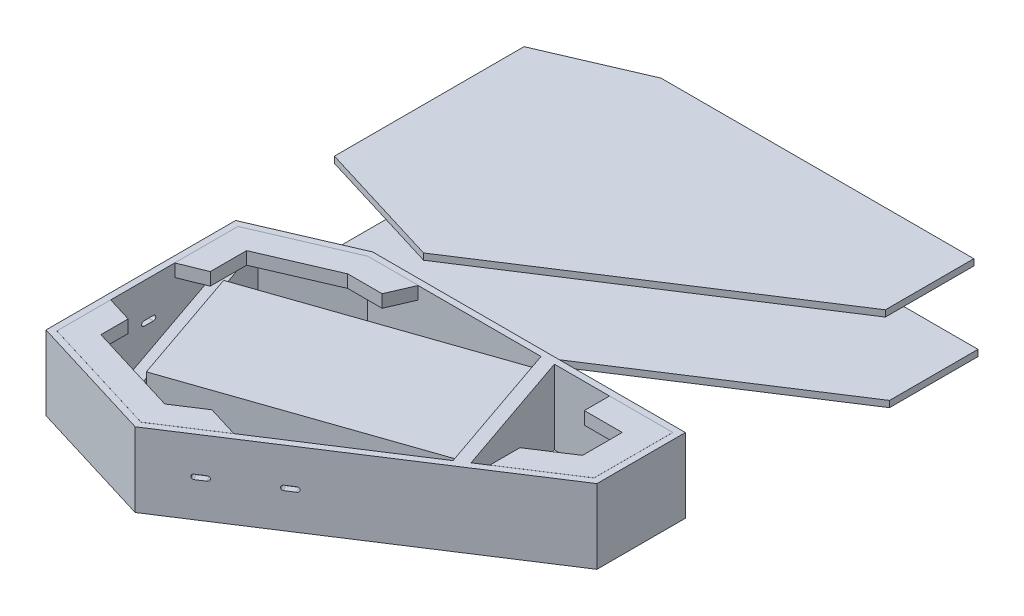
SolidWorks part; units mm, degrees
ref_plane "Front Plane" through (0, 0, 0) normal (0, 0, 1) x (1, 0, 0)
ref_plane "Top Plane" through (0, 0, 0) normal (0, 1, 0) x (1, 0, 0)
ref_plane "Right Plane" through (0, 0, 0) normal (1, 0, 0) x (0, 0, -1)
sketch "Sketch1" plane through (0, 0, 0) normal (0, 1, 0) x (1, 0, 0)
  line L0 (89.8686, 45.6481) -> (404.1936, 45.6481)
  line L1 (404.1936, 45.6481) -> (404.1936, -43.2519)
  line L2 (404.1936, -43.2519) -> (122.6914, -225.8144)
  line L3 (122.6914, -225.8144) -> (-6.35, -186.3625)
  line L4 (-6.35, -186.3625) -> (-6.35, 4.1778)
  line L5 (-6.35, 4.1778) -> (89.8686, 45.6481)
  line L6 (0, 0) -> (91.1788, 39.2981)
  line L7 (91.1788, 39.2981) -> (397.8436, 39.2981)
  line L8 (397.8436, 39.2981) -> (397.8436, -39.8016)
  line L9 (397.8436, -39.8016) -> (121.7185, -218.8769)
  line L10 (121.7185, -218.8769) -> (0, -181.6638)
  line L11 (0, -181.6638) -> (0, 0)
  dimension "D1" = 107
  dimension "D2" = 271.4625
  dimension "D3" = 88.9
  dimension "D4" = 134.9375
  dimension "D5" = 190.5403
  dimension "D6" = 6.35
  dimension "D7" = 90
  dimension "D8" = 104.775
  dimension "D9" = 156.684
  dimension "D10" = 113.316
  dimension "D11" = 314.325
  dimension "D12" = 335.5184
extrude "Boss-Extrude1" add sketch "Sketch1" along normal blind 74.6125
sketch "Sketch2" plane through (52.7123, 0, 182.2717) normal (0, 1, 0) x (1, 0, 0)
  line L0 (-17.463, 132.8126) -> (214.2931, 212.6127)
  line L1 (214.2931, 212.6127) -> (255.0614, 94.2129)
  line L2 (255.0614, 94.2129) -> (23.3053, 14.4129)
  line L3 (23.3053, 14.4129) -> (-17.463, 132.8126)
  dimension "D1" = 245.11
  dimension "D2" = 125.222
extrude "Boss-Extrude2" add sketch "Sketch2" along normal blind 70.104 separate body
sketch "Sketch6" plane through (-0.5794, 0, -0.1179) normal (0, 1, 0) x (1, 0, 0)
  line L0 (91.8141, 39.2981) -> (0.6353, 0)
  line L1 (0.6353, 0) -> (0.6353, -63.5)
  line L3 (0.6353, -63.5) -> (26.0353, -53.2238)
  line L4 (26.0353, -53.2238) -> (26.0353, -16.7113)
  line L5 (26.0353, -16.7113) -> (97.0547, 13.8981)
  line L6 (97.0547, 13.8981) -> (131.6469, 13.8981)
  line L7 (131.6469, 13.8981) -> (142.6141, 39.2981)
  line L9 (142.6141, 39.2981) -> (91.8141, 39.2981)
  dimension "D1" = 63.5
  dimension "D2" = 25.4
  dimension "D3" = 25.4
  dimension "D4" = 25.4
  dimension "D5" = 50.8
  dimension "D6" = 36.5125
extrude "Boss-Extrude3" add sketch "Sketch6" along normal blind 12.7
sketch "Sketch8" plane through (0, 0, -81.2312) normal (0, 1, 0) x (1, 0, 0)
  line L0 (0, -262.9438) -> (121.7185, -300.1569)
  line L1 (121.7185, -300.1569) -> (178.2807, -263.4746)
  line L3 (178.2807, -263.4746) -> (146.5557, -253.7753)
  line L4 (146.5557, -253.7753) -> (117.8272, -272.4066)
  line L5 (117.8272, -272.4066) -> (25.4, -244.1487)
  line L6 (25.4, -244.1487) -> (25.4, -216.7343)
  line L7 (25.4, -216.7343) -> (0, -208.9688)
  line L9 (0, -208.9688) -> (0, -262.9438)
  dimension "D1" = 25.4
  dimension "D2" = 25.4
  dimension "D3" = 53.975
  dimension "D4" = 25.4
extrude "Boss-Extrude4" add sketch "Sketch8" along normal blind 12.7
sketch "Sketch9" plane through (0, 0, 0) normal (0, 1, 0) x (1, 0, 0)
  line L0 (397.8436, 39.2981) -> (334.3436, 39.2981)
  line L2 (334.3436, 39.2981) -> (334.3436, 13.8981)
  line L3 (334.3436, 13.8981) -> (372.4436, 13.8981)
  line L4 (372.4436, 13.8981) -> (372.4436, -26.0004)
  line L5 (372.4436, -26.0004) -> (334.3436, -50.7093)
  line L6 (334.3436, -50.7093) -> (334.3436, -80.9832)
  line L8 (334.3436, -80.9832) -> (397.8436, -39.8016)
  line L9 (397.8436, -39.8016) -> (397.8436, 39.2981)
  dimension "D1" = 25.4
  dimension "D2" = 25.4
  dimension "D3" = 25.4
  dimension "D4" = 63.5
extrude "Boss-Extrude5" add sketch "Sketch9" along normal blind 12.7
pattern_linear "LPattern2" count 2 spacing 61.976 along (0, 1, 0) of "Boss-Extrude3"
pattern_linear "LPattern3" count 2 spacing 61.976 along (0, 1, 0) of "Boss-Extrude4"
pattern_linear "LPattern4" count 2 spacing 61.976 along (0, 1, 0) of "Boss-Extrude5"
sketch "Sketch12" plane through (139.414, 0, 214.9693) normal (0.5441, 0, 0.839) x (0.839, 0, -0.5441)
  line L0 (-19.9314, 74.6125) -> (315.587, 74.6125) construction
  line L2 (22.9311, 37.3062) -> (32.4561, 37.3062) construction
  line L3 (22.9311, 39.6875) -> (32.4561, 39.6875)
  line L4 (22.9311, 34.925) -> (32.4561, 34.925)
  line L5 (88.0186, 37.3062) -> (97.5436, 37.3062) construction
  line L6 (88.0186, 39.6875) -> (97.5436, 39.6875)
  line L7 (88.0186, 34.925) -> (97.5436, 34.925)
  arc A0 (22.9311, 39.6875) -> (22.9311, 34.925) centre (22.9311, 37.3062) ccw
  arc A1 (32.4561, 34.925) -> (32.4561, 39.6875) centre (32.4561, 37.3062) ccw
  arc A2 (88.0186, 39.6875) -> (88.0186, 34.925) centre (88.0186, 37.3062) ccw
  arc A3 (97.5436, 34.925) -> (97.5436, 39.6875) centre (97.5436, 37.3062) ccw
  point P6 (27.6936, 37.3062)
  point P11 (92.7811, 37.3062)
  dimension "D1" = 37.3062
  dimension "D2" = 65.0875
  dimension "D3" = 37.3062
extrude "Cut-Extrude1" cut sketch "Sketch12" against normal blind 6.604
sketch "Sketch14" plane through (-6.35, 0, 0) normal (-1, 0, 0) x (0, 0, 1)
  line L0 (149.85, 37.2745) -> (159.375, 37.2745) construction
  line L1 (149.85, 39.6558) -> (159.375, 39.6558)
  line L2 (149.85, 34.8933) -> (159.375, 34.8933)
  line L3 (84.7625, 37.2745) -> (94.2875, 37.2745) construction
  line L4 (84.7625, 39.6558) -> (94.2875, 39.6558)
  line L5 (84.7625, 34.8933) -> (94.2875, 34.8933)
  line L6 (-4.1778, 74.6125) -> (186.3625, 74.6125) construction
  line L7 (186.3625, 74.6125) -> (186.3625, 0) construction
  arc A0 (149.85, 39.6558) -> (149.85, 34.8933) centre (149.85, 37.2745) ccw
  arc A1 (159.375, 34.8933) -> (159.375, 39.6558) centre (159.375, 37.2745) ccw
  arc A2 (84.7625, 39.6558) -> (84.7625, 34.8933) centre (84.7625, 37.2745) ccw
  arc A3 (94.2875, 34.8933) -> (94.2875, 39.6558) centre (94.2875, 37.2745) ccw
  point P2 (154.6125, 37.2745)
  point P7 (89.525, 37.2745)
  dimension "D3" = 31.75
  dimension "D1" = 65.0875
  dimension "D2" = 37.338
extrude "Cut-Extrude2" cut sketch "Sketch14" against normal blind 6.604
sketch "Sketch15" plane through (0, 0, 0) normal (0, 1, 0) x (1, 0, 0)
  line L0 (311.8707, -95.5576) -> (265.4361, 39.2981)
  line L1 (178.2296, -182.2278) -> (334.3436, -80.9832) construction
  line L2 (334.3436, 39.2981) -> (141.9837, 39.2981) construction
  line L4 (322.8506, -88.4368) -> (278.8679, 39.2981)
  line L5 (322.8506, -88.4368) -> (311.8707, -95.5576)
  line L6 (278.8679, 39.2981) -> (265.4361, 39.2981)
  dimension "D1" = 12.7
extrude "Boss-Extrude6" add sketch "Sketch15" along normal up to surface (74.6125 mm away) up to face at (168.0412, 74.6125, 59.9925)
sketch "Sketch17" plane through (0, 12.7, 0) normal (0, 1, 0) x (1, 0, 0)
  line L0 (88.2589, -208.6472) -> (14.2946, 6.161)
  line L1 (0, -181.6638) -> (121.7185, -218.8769) construction
  line L2 (91.1788, 39.2981) -> (0.0559, 0.0241) construction
  line L4 (88.2589, -208.6472) -> (73.1104, -204.0159)
  line L5 (73.1104, -204.0159) -> (2.4923, 1.0742)
  line L6 (2.4923, 1.0742) -> (14.2946, 6.161)
  dimension "D1" = 12.8154
extrude "Boss-Extrude7" add sketch "Sketch17" along normal up to surface (49.276 mm away) up to face at (76.8914, 61.976, 171.5807)
sketch "Sketch18" plane through (0, 74.6125, 0) normal (0, 1, 0) x (1, 0, 0)
  line L0 (404.1936, 246.5969) -> (122.6914, 64.0344)
  line L1 (122.6914, 64.0344) -> (-6.35, 103.4863)
  line L2 (-6.35, 103.4863) -> (-6.35, 294.0266)
  line L3 (-6.35, 294.0266) -> (89.8686, 335.4969)
  line L4 (89.8686, 335.4969) -> (404.1936, 335.4969)
  line L5 (404.1936, 335.4969) -> (404.1936, 246.5969)
extrude "Boss-Extrude8" add sketch "Sketch18" along normal blind 6.35
sketch "Sketch19" plane through (0, 0, 0) normal (0, -1, 0) x (1, 0, 0)
  line L0 (122.6914, -68.2179) -> (-6.35, -107.6698)
  line L1 (-6.35, -107.6698) -> (-6.35, -298.2101)
  line L2 (-6.35, -298.2101) -> (89.8686, -339.6804)
  line L3 (89.8686, -339.6804) -> (404.1936, -339.6804)
  line L4 (404.1936, -339.6804) -> (404.1936, -250.7804)
  line L5 (404.1936, -250.7804) -> (122.6914, -68.2179)
  dimension "D1" = 156.684
  dimension "D2" = 107
  dimension "D3" = 130.035
  dimension "D4" = 88.9
  dimension "D5" = 190.5403
extrude "Boss-Extrude9" add sketch "Sketch19" along normal blind 6.35 separate body
